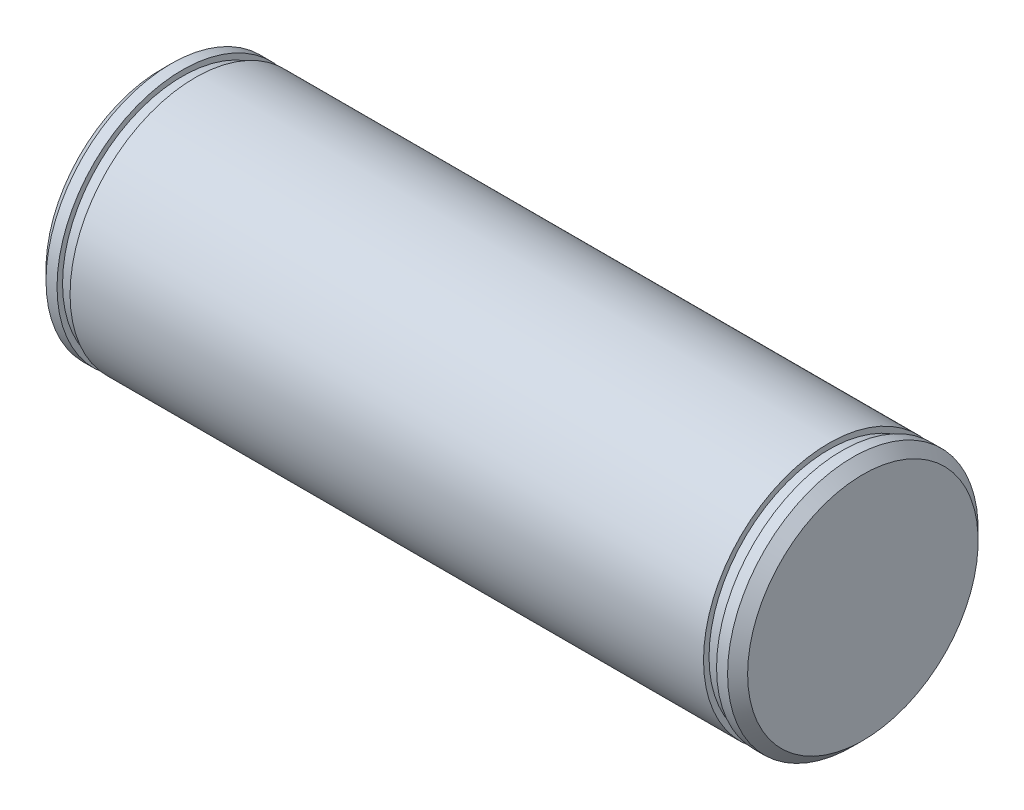
SolidWorks part; units mm, degrees
material "45"
ref_plane "前视基准面" through (0, 0, 0) normal (0, 0, 1) x (1, 0, 0)
ref_plane "上视基准面" through (0, 0, 0) normal (0, 1, 0) x (1, 0, 0)
ref_plane "右视基准面" through (0, 0, 0) normal (1, 0, 0) x (0, 0, -1)
sketch "草图1" plane through (0, 0, 0) normal (0, 0, 1) x (1, 0, 0)
  line L0 (0, 0) -> (172.3923, 0) construction
  line L1 (0, 0) -> (0, 12.5)
  line L2 (0, 12.5) -> (2.1, 12.5)
  line L3 (2.1, 12.5) -> (2.1, 11.95)
  line L4 (2.1, 11.95) -> (3.4, 11.95)
  line L5 (3.4, 11.95) -> (3.4, 12.5)
  line L6 (3.4, 12.5) -> (66.6, 12.5)
  line L7 (66.6, 12.5) -> (66.6, 11.95)
  line L8 (66.6, 11.95) -> (67.9, 11.95)
  line L9 (67.9, 11.95) -> (67.9, 12.5)
  line L10 (67.9, 12.5) -> (70, 12.5)
  line L11 (70, 12.5) -> (70, 0)
  line L12 (0, 0) -> (70, 0)
  dimension "D1" = 70
  dimension "D2" = 25
  dimension "D3" = 2.1
  dimension "D4" = 1.3
  dimension "D5" = 23.9
revolve "旋转1" add sketch "草图1" angle 360 about L0
chamfer "倒角1" distance 1 2 edges at (0, 0, 12.5) (70, 0, 12.5)
